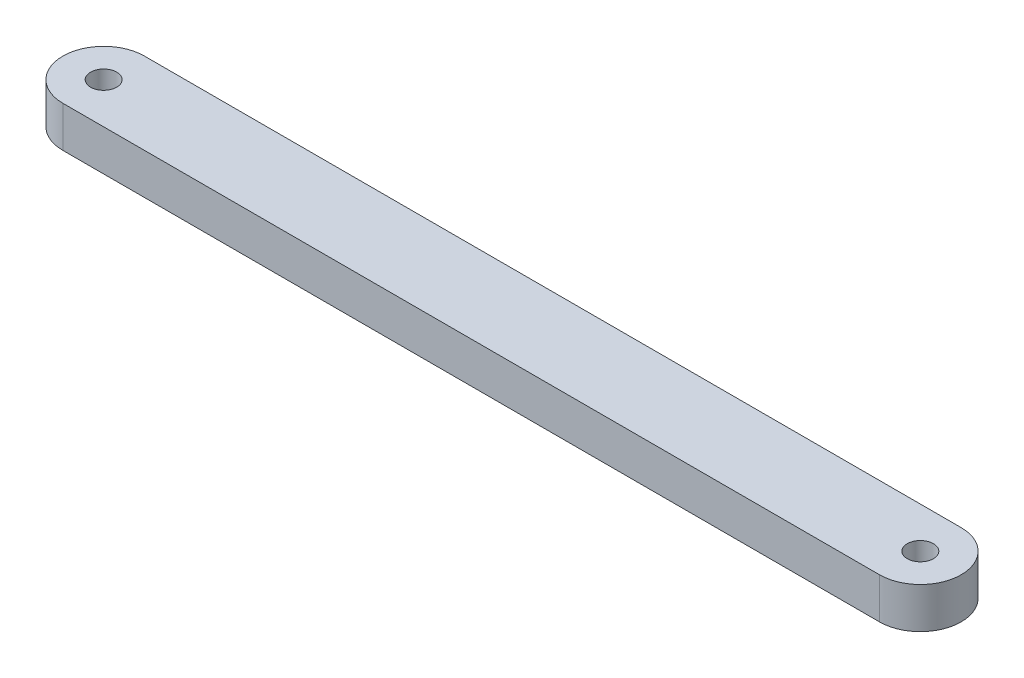
SolidWorks part; units mm, degrees
ref_plane "正面" through (0, 0, 0) normal (0, 0, 1) x (1, 0, 0)
ref_plane "平面" through (0, 0, 0) normal (0, 1, 0) x (1, 0, 0)
ref_plane "右側面" through (0, 0, 0) normal (1, 0, 0) x (0, 0, -1)
sketch "ｽｹｯﾁ1" plane through (0, 0, 0) normal (0, 1, 0) x (1, 0, 0)
  line L0 (0, 0) -> (110, 0) construction
  line L1 (0, -5) -> (100, -5)
  line L3 (0, 5) -> (100, 5)
  circle A0 centre (0, 0) radius 1.6
  circle A1 centre (100, 0) radius 1.6
  arc A2 (0, 5) -> (0, -5) centre (0, 0) ccw
  arc A3 (100, -5) -> (100, 5) centre (100, 0) ccw
  dimension "D5" = 3.2
  dimension "D1" = 5
  dimension "D2" = 10
  dimension "D4" = 100
extrude "ﾎﾞｽ - 押し出し1" add sketch "ｽｹｯﾁ1" along normal blind 5
